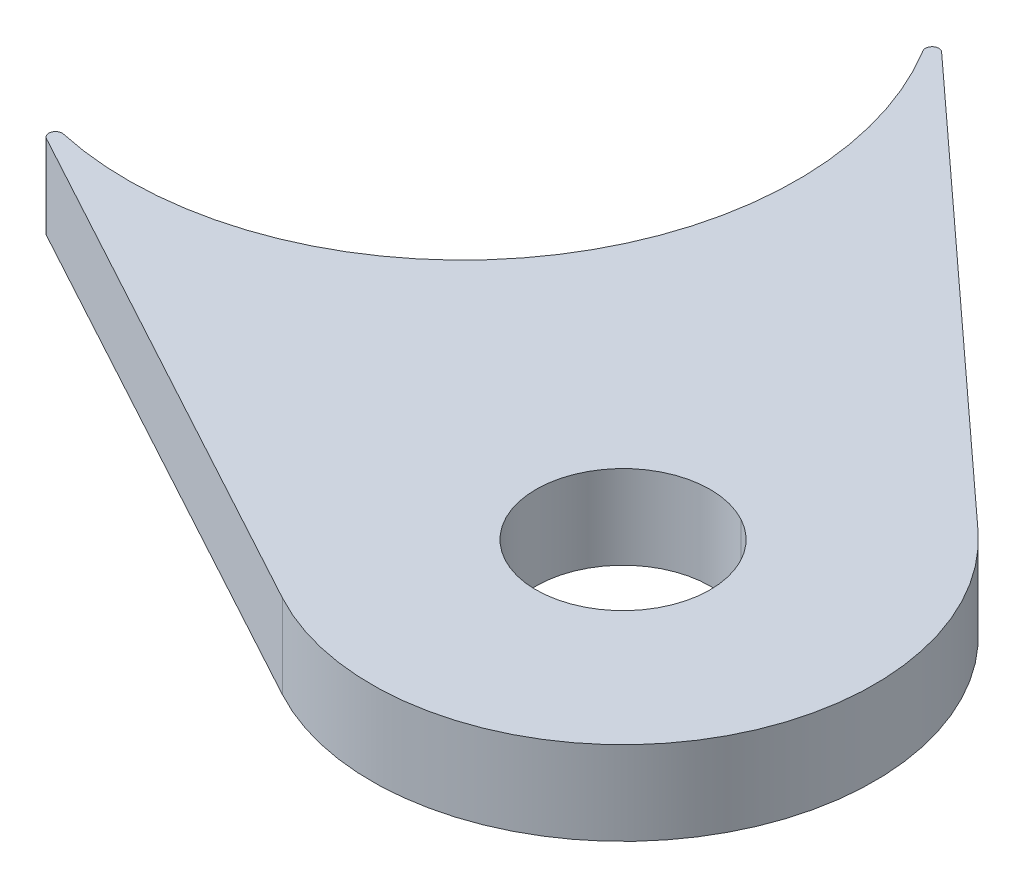
SolidWorks part; units mm, degrees
material "AISI 4130 Steel, annealed at 865C"
ref_plane "X-Y Datum" through (0, 0, 0) normal (0, 0, 1) x (1, 0, 0)
ref_plane "X-Z Datum" through (0, 0, 0) normal (0, 1, 0) x (1, 0, 0)
ref_plane "Y-Z Datum" through (0, 0, 0) normal (1, 0, 0) x (0, 0, -1)
sketch "Sketch1" plane through (0, 0, 0) normal (0, 1, 0) x (1, 0, 0)
  line L0 (16.6587, -23.4844) -> (-6.0555, -11.1634)
  line L1 (27.6336, -8.0878) -> (8.5778, 9.3654)
  circle A2 centre (21.2003, -15.1119) radius 3.3
  circle A3 centre (0, 0) radius 12.7 construction
  circle A4 centre (21.2003, -15.1119) radius 9.525 construction
  arc A6 (27.6336, -8.0878) -> (16.6587, -23.4844) centre (21.2003, -15.1119) cw
  arc A7 (-6.0555, -11.1634) -> (8.5778, 9.3654) centre (0, 0) ccw
  dimension "D3" = 25.4
  dimension "D4" = 19.05
  dimension "D5" = 6.6
  dimension "D1" = 26.035
extrude "Boss-Extrude1" add sketch "Sketch1" along normal blind 3.175
fillet "Fillet1" radius 0.254 2 edges at (8.5778, 1.5875, -9.3654) (-6.0555, 1.5875, 11.1634)
ref_point "Point1"
ref_plane "Plane1" through (22.7141, 0, 12.3211) normal (0.879, 0, 0.4768) x (0.4768, 0, -0.879)
split line "Split Line1"
